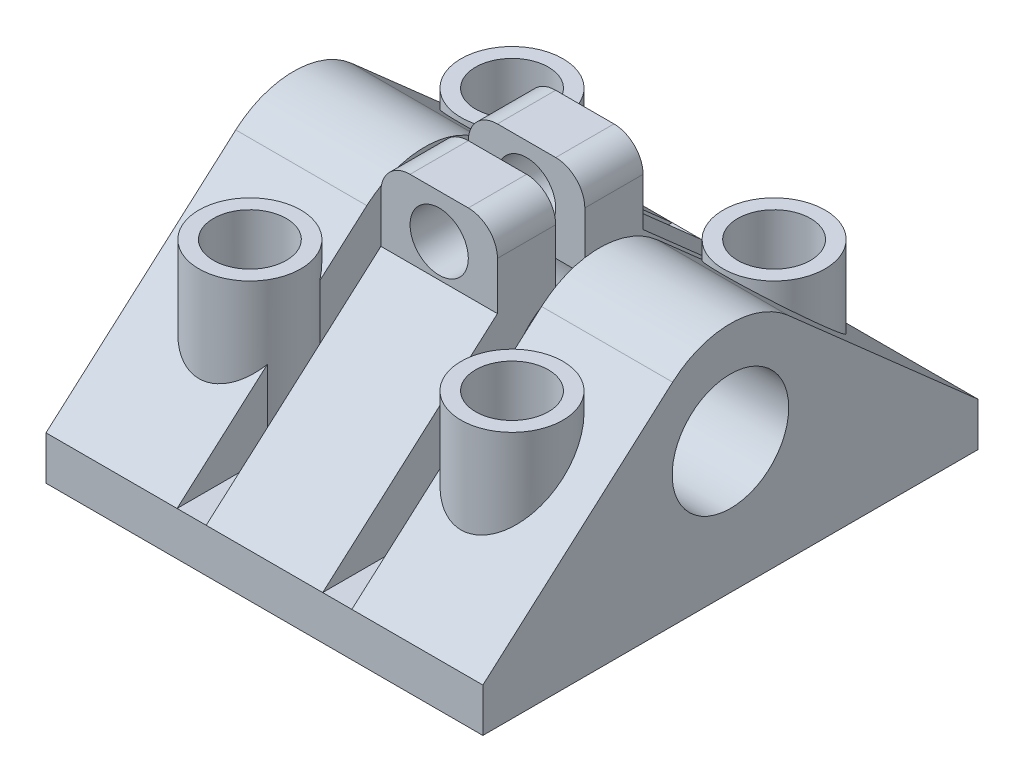
SolidWorks part; units mm, degrees
ref_plane "Front Plane" through (0, 0, 0) normal (0, 0, 1) x (1, 0, 0)
ref_plane "Top Plane" through (0, 0, 0) normal (0, 1, 0) x (1, 0, 0)
ref_plane "Right Plane" through (0, 0, 0) normal (1, 0, 0) x (0, 0, -1)
sketch "Sketch1" plane through (0, 0, 0) normal (0, 1, 0) x (1, 0, 0)
  line L1 (0, 0) -> (30, 0)
  line L2 (0, 0) -> (0, 34)
  line L3 (0, 34) -> (30, 34)
  line L4 (30, 0) -> (30, 34)
  circle A0 centre (6, 26) radius 2.5
  circle A1 centre (24, 26) radius 2.5
  circle A2 centre (6, 8) radius 2.5
  circle A3 centre (24, 8) radius 2.5
  dimension "D3" = 5
  dimension "D4" = 5
  dimension "D5" = 5
  dimension "D6" = 5
  dimension "D1" = 34
  dimension "D2" = 30
  dimension "D7" = 18
  dimension "D8" = 18
  dimension "D9" = 18
  dimension "D10" = 18
  dimension "D11" = 0
  dimension "D12" = 8
  dimension "D13" = 6
extrude "Boss-Extrude1" add sketch "Sketch1" along normal blind 3
sketch "Sketch2" plane through (30, 0, 0) normal (1, 0, 0) x (0, 0, -1)
  line L0 (34, 3) -> (34, 0) construction
  line L1 (0, 3) -> (0, 0) construction
  line L2 (0, 3) -> (34, 3) construction
  line L3 (34, 3) -> (20.9697, 14.4973)
  line L4 (13.0303, 14.4973) -> (0, 3)
  line L5 (0, 3) -> (34, 3)
  circle A0 centre (17, 9) radius 4
  arc A1 (13.0303, 14.4973) -> (20.9697, 14.4973) centre (17, 9.9983) cw
  point P15 (17, 18)
  dimension "D3" = 8
  dimension "D6" = 6
  dimension "D1" = 17
  dimension "D2" = 17
  dimension "D4" = 6
  dimension "D5" = 15
extrude "Boss-Extrude2" add sketch "Sketch2" against normal through all
sketch "Sketch3" plane through (0, 0, 0) normal (0, -1, 0) x (1, 0, 0)
  circle A0 centre (6, -8) radius 2.5
  circle A1 centre (24, -8) radius 2.5
  circle A2 centre (24, -26) radius 2.5
  circle A3 centre (6, -26) radius 2.5
extrude "Cut-Extrude1" cut sketch "Sketch3" against normal through all
sketch "Sketch4" plane through (0, 0, 0) normal (0, 0, 1) x (1, 0, 0)
  line L0 (0, 3) -> (30, 3) construction
  line L1 (9, 16.407) -> (11, 16.407)
  line L2 (9, 16.407) -> (9, 3)
  line L3 (9, 3) -> (11, 3)
  line L4 (11, 16.407) -> (11, 3)
  line L5 (0, 14.4973) -> (0, 3) construction
  line L6 (19, 16.407) -> (21, 16.407)
  line L7 (19, 16.407) -> (19, 3)
  line L8 (19, 3) -> (21, 3)
  line L9 (21, 16.407) -> (21, 3)
  line L10 (30, 14.4973) -> (30, 3) construction
  dimension "D1" = 2
  dimension "D2" = 2
  dimension "D3" = 9
  dimension "D4" = 9
extrude "Cut-Extrude2" cut sketch "Sketch4" against normal through all
sketch "Sketch5" plane through (11, 0, 0) normal (-1, 0, 0) x (0, 0, 1)
  line L0 (0, 3) -> (0, 0) construction
  line L1 (-18, 16.5101) -> (-16, 16.5101)
  line L2 (-18, 16.5101) -> (-18, 11.957)
  line L3 (-18, 11.957) -> (-16, 11.957)
  line L4 (-16, 16.5101) -> (-16, 11.957)
  line L5 (-34, 3) -> (-34, 0) construction
  dimension "D1" = 2
  dimension "D2" = 16
  dimension "D3" = 16
extrude "Cut-Extrude3" cut sketch "Sketch5" against normal up to next
sketch "Sketch6" plane through (11, 0, 0) normal (-1, 0, 0) x (0, 0, 1)
  line L1 (-16, 12.873) -> (-12, 12.873)
  line L2 (-16, 12.873) -> (-16, 18.873)
  line L3 (-16, 18.873) -> (-12, 18.873)
  line L4 (-12, 12.873) -> (-12, 18.873)
  line L5 (-18, 12.873) -> (-22, 12.873)
  line L6 (-18, 12.873) -> (-18, 18.871)
  line L7 (-18, 18.871) -> (-22, 18.871)
  line L8 (-22, 12.873) -> (-22, 18.871)
  dimension "D1" = 6
  dimension "D2" = 5.998
  dimension "D3" = 4
  dimension "D4" = 4
extrude "Boss-Extrude3" add sketch "Sketch6" against normal blind 8
sketch "Sketch7" plane through (0, 0, -12) normal (0, 0, 1) x (1, 0, 0)
  line L0 (19, 13.5882) -> (19, 18.873) construction
  line L1 (19, 18.873) -> (11, 18.873) construction
  circle A0 centre (15, 15.873) radius 2
  dimension "D1" = 4
  dimension "D2" = 4
  dimension "D3" = 3
extrude "Cut-Extrude4" cut sketch "Sketch7" against normal through all
fillet "Fillet1" radius 2 4 edges at (11, 18.871, -20) (19, 18.871, -20) (11, 18.873, -14) (19, 18.873, -14)
sketch "Sketch8" plane through (0, 0, 0) normal (0, -1, 0) x (-1, 0, 0)
  circle A0 centre (-6, 8) radius 2.5
  circle A1 centre (-6, 8) radius 3.5
  circle A2 centre (-24, 8) radius 2.5
  circle A3 centre (-24, 8) radius 3.5
  circle A4 centre (-6, 26) radius 2.5
  circle A5 centre (-6, 26) radius 3.5
  circle A6 centre (-24, 26) radius 2.5
  circle A7 centre (-24, 26) radius 3.5
  dimension "D1" = 7
  dimension "D2" = 7
  dimension "D3" = 7
  dimension "D4" = 7
extrude "Boss-Extrude4" add sketch "Sketch8" against normal blind 13.5
